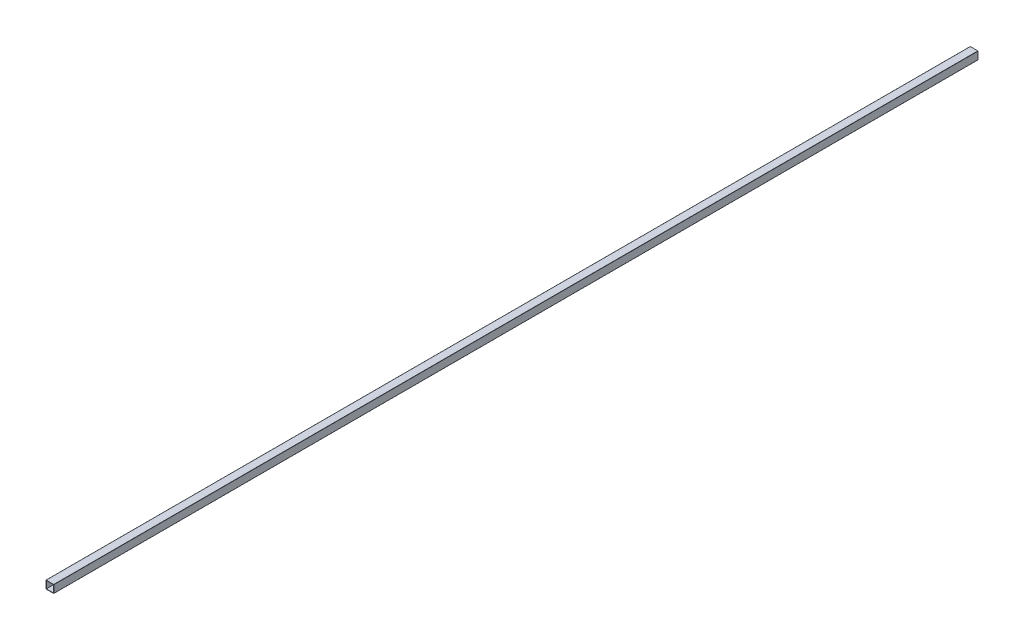
SolidWorks part; units mm, degrees
ref_plane "Alzado" through (0, 0, 0) normal (0, 0, 1) x (1, 0, 0)
ref_plane "Planta" through (0, 0, 0) normal (0, 1, 0) x (1, 0, 0)
ref_plane "Vista lateral" through (0, 0, 0) normal (1, 0, 0) x (0, 0, -1)
sketch "Croquis1" plane through (0, 0, 0) normal (0, 0, 1) x (1, 0, 0)
  line L0 (-23.51, -23.51) -> (-23.51, 23.51)
  line L1 (-24.4, -25.4) -> (24.4, -25.4)
  line L2 (-25.4, -24.4) -> (-25.4, 24.4)
  line L3 (-24.4, 25.4) -> (24.4, 25.4)
  line L4 (25.4, -24.4) -> (25.4, 24.4)
  line L5 (-25.4, -25.4) -> (25.4, 25.4) construction
  line L6 (-25.4, 25.4) -> (25.4, -25.4) construction
  line L7 (-23.51, 23.51) -> (23.51, 23.51)
  line L8 (23.51, -23.51) -> (23.51, 23.51)
  line L9 (-23.51, -23.51) -> (23.51, -23.51)
  line L10 (-25.4, 25.4) -> (25.4, 25.4) construction
  line L11 (25.4, -25.4) -> (25.4, 25.4) construction
  line L12 (-25.4, -25.4) -> (25.4, -25.4) construction
  line L13 (-25.4, -25.4) -> (-25.4, 25.4) construction
  arc A0 (25.4, -24.4) -> (24.4, -25.4) centre (24.4, -24.4) cw
  arc A1 (25.4, 24.4) -> (24.4, 25.4) centre (24.4, 24.4) ccw
  arc A2 (-25.4, -24.4) -> (-24.4, -25.4) centre (-24.4, -24.4) ccw
  arc A3 (-24.4, 25.4) -> (-25.4, 24.4) centre (-24.4, 24.4) ccw
  point P0 (0, 0)
  dimension "D2" = 1
  dimension "D1" = 50.8
  dimension "D3" = 1.89
extrude "Saliente-Extruir1" add sketch "Croquis1" along normal blind 6000
